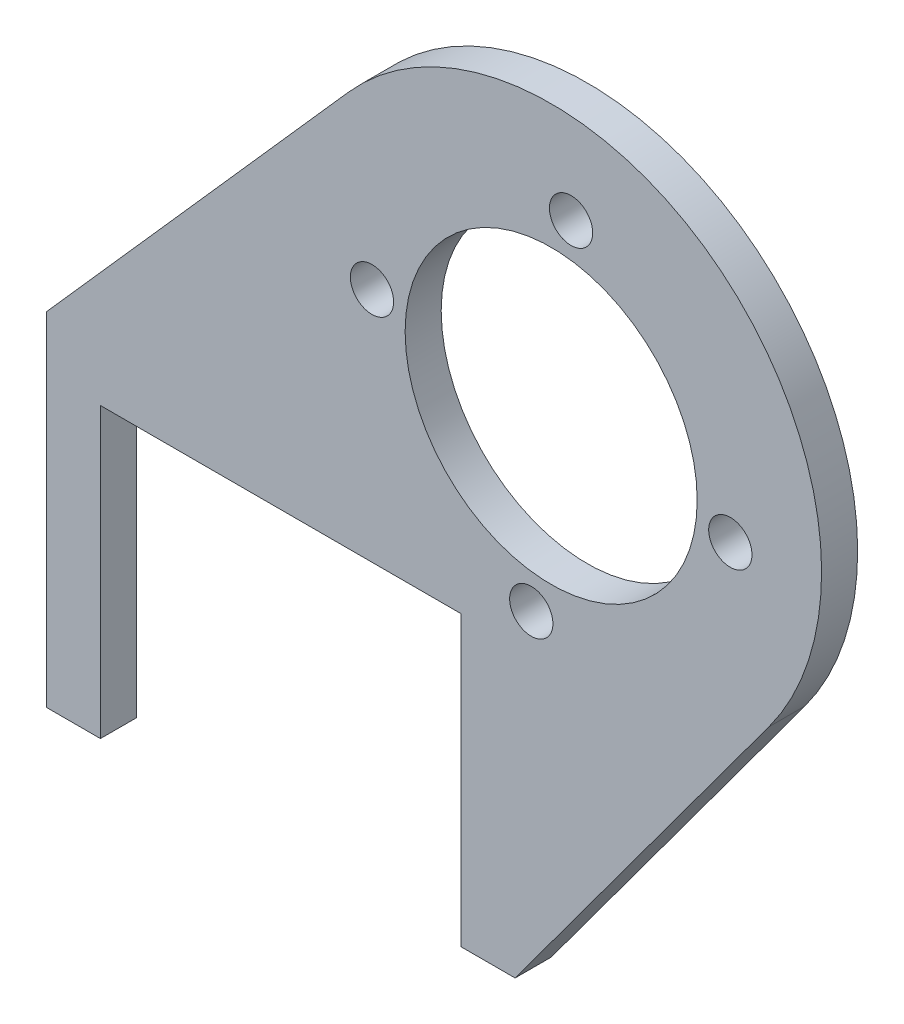
SolidWorks part; units mm, degrees
ref_plane "Plan de face" through (0, 0, 0) normal (0, 0, 1) x (1, 0, 0)
ref_plane "Plan de dessus" through (0, 0, 0) normal (0, 1, 0) x (1, 0, 0)
ref_plane "Plan de droite" through (0, 0, 0) normal (1, 0, 0) x (0, 0, -1)
sketch "Esquisse1" plane through (0, 0, 0) normal (0, 0, 1) x (1, 0, 0)
  line L0 (-65, 0) -> (-40.5, 0) construction
  line L1 (-40.5, 0) -> (40.5, 0) construction
  line L2 (-125, -60) -> (-125, -45) construction
  line L3 (-25, -140) -> (-10, -140)
  line L4 (-140, -140) -> (-125, -140)
  line L5 (-125, -140) -> (-125, -60)
  line L6 (-125, -60) -> (-25, -60)
  line L7 (-25, -60) -> (-25, -140)
  line L8 (-10, -140) -> (60.3782, -44.4913)
  line L9 (-56.1576, 49.7124) -> (-140, -45)
  line L10 (0, 0) -> (-75, -60) construction
  line L11 (-25, -140) -> (-125, -140) construction
  line L12 (0, 0) -> (-49.6867, 5.5207) construction
  line L13 (-140, -45) -> (-140, -140)
  line L14 (-140, -45) -> (-125, -45) construction
  line L15 (-125, -60) -> (-140, -45) construction
  circle A0 centre (0, 0) radius 40.5
  arc A1 (-56.1576, 49.7124) -> (60.3782, -44.4913) centre (0, 0) cw
  circle A4 centre (0, 0) radius 49.9924 construction
  circle A5 centre (-49.6867, 5.5207) radius 6
  circle A6 centre (5.5207, 49.6867) radius 6
  circle A7 centre (49.6867, -5.5207) radius 6
  circle A8 centre (-5.5207, -49.6867) radius 6
  point P10 (-75, -60)
  point P31 (0, 0)
  dimension "D1" = 75
  dimension "D2" = 81
  dimension "D5" = 15
  dimension "D6" = 12
  dimension "D3" = 100
  dimension "D4" = 80
  dimension "D8" = 45
  dimension "D9" = 70.7
  dimension "D10" = 60
  dimension "D11" = 15
  dimension "D12" = 75
  dimension "D7" = 4
extrude "Boss.-Extru.1" add sketch "Esquisse1" along normal blind 10
